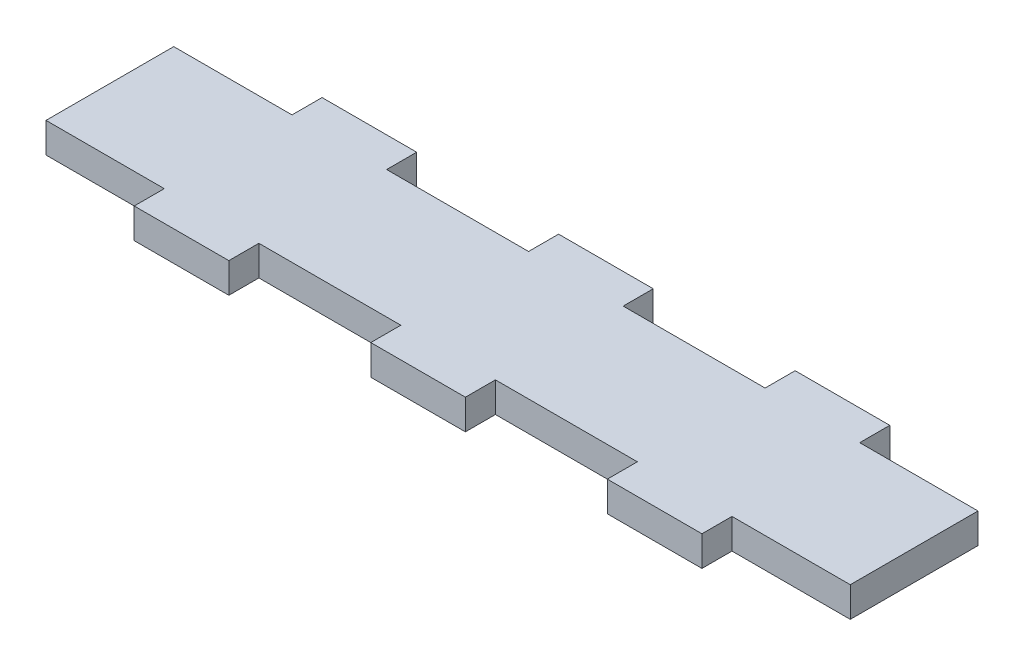
SolidWorks part; units mm, degrees
ref_plane "Front Plane" through (0, 0, 0) normal (0, 0, 1) x (1, 0, 0)
ref_plane "Top Plane" through (0, 0, 0) normal (0, 1, 0) x (1, 0, 0)
ref_plane "Right Plane" through (0, 0, 0) normal (1, 0, 0) x (0, 0, -1)
sketch "Sketch1" plane through (0, 0, 0) normal (0, 1, 0) x (1, 0, 0)
  line L0 (-85, 13.5) -> (-60, 13.5)
  line L1 (-85, 13.5) -> (85, 13.5) construction
  line L2 (-85, 13.5) -> (-85, -13.5)
  line L3 (-85, -13.5) -> (85, -13.5) construction
  line L4 (85, 13.5) -> (85, -13.5)
  line L5 (-85, 13.5) -> (85, -13.5) construction
  line L6 (-85, -13.5) -> (85, 13.5) construction
  line L7 (-60, 13.5) -> (-60, 19.85)
  line L8 (-60, 19.85) -> (-40, 19.85)
  line L9 (-40, 19.85) -> (-40, 13.5)
  line L10 (-40, 13.5) -> (-10, 13.5)
  line L11 (-10, 13.5) -> (-10, 19.85)
  line L12 (-10, 19.85) -> (10, 19.85)
  line L13 (10, 19.85) -> (10, 13.5)
  line L14 (10, 13.5) -> (40, 13.5)
  line L15 (40, 13.5) -> (40, 19.85)
  line L16 (40, 19.85) -> (60, 19.85)
  line L17 (60, 19.85) -> (60, 13.5)
  line L18 (60, 13.5) -> (85, 13.5)
  line L19 (-85, 0) -> (85, 0) construction
  line L20 (-85, -13.5) -> (-60, -13.5)
  line L21 (60, -13.5) -> (85, -13.5)
  line L22 (60, -19.85) -> (60, -13.5)
  line L23 (40, -19.85) -> (60, -19.85)
  line L24 (40, -13.5) -> (40, -19.85)
  line L25 (10, -13.5) -> (40, -13.5)
  line L26 (10, -19.85) -> (10, -13.5)
  line L27 (-10, -19.85) -> (10, -19.85)
  line L28 (-10, -13.5) -> (-10, -19.85)
  line L29 (-40, -13.5) -> (-10, -13.5)
  line L30 (-40, -19.85) -> (-40, -13.5)
  line L31 (-60, -19.85) -> (-40, -19.85)
  line L32 (-60, -13.5) -> (-60, -19.85)
  point P0 (0, 0)
  point P13 (0, 19.85)
  dimension "D1" = 170
  dimension "D2" = 20
  dimension "D3" = 30
  dimension "D4" = 6.35
  dimension "D5" = 27
extrude "Boss-Extrude1" add sketch "Sketch1" along normal blind 6.35
